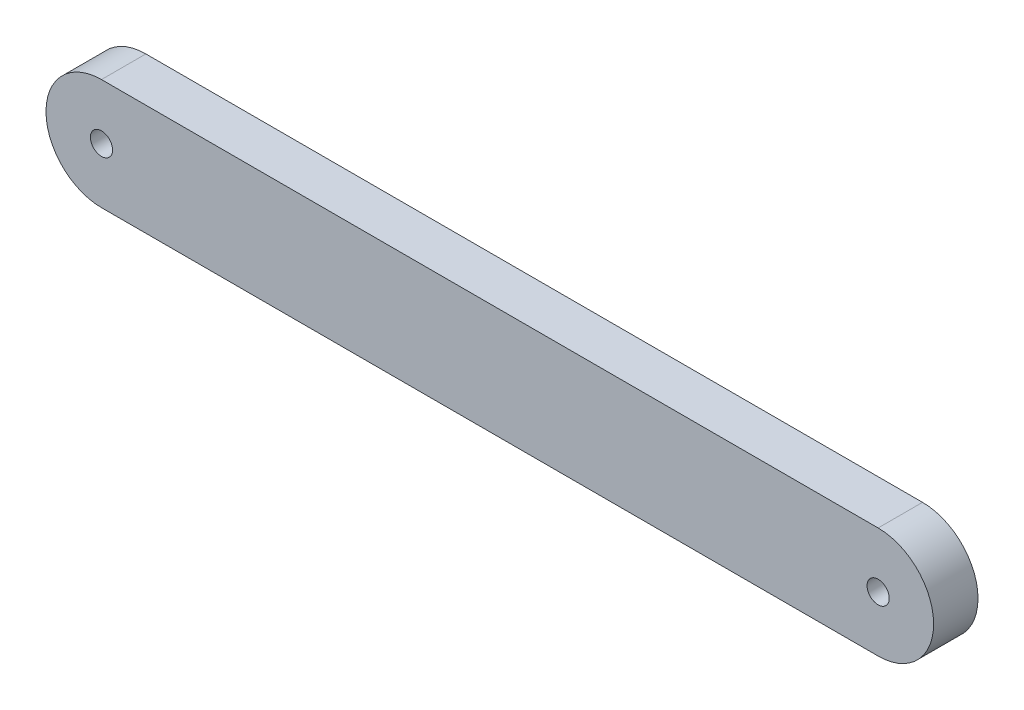
SolidWorks part; units mm, degrees
ref_plane "Front Plane" through (0, 0, 0) normal (0, 0, 1) x (1, 0, 0)
ref_plane "Top Plane" through (0, 0, 0) normal (0, 1, 0) x (1, 0, 0)
ref_plane "Right Plane" through (0, 0, 0) normal (1, 0, 0) x (0, 0, -1)
sketch "Sketch1" plane through (0, 0, 0) normal (0, 0, 1) x (1, 0, 0)
  line L0 (-444.5, 0) -> (444.5, 0) construction
  line L1 (-444.5, 63.5) -> (444.5, 63.5)
  line L2 (-444.5, -63.5) -> (444.5, -63.5)
  arc A0 (-444.5, 63.5) -> (-444.5, -63.5) centre (-444.5, 0) ccw
  arc A1 (444.5, -63.5) -> (444.5, 63.5) centre (444.5, 0) ccw
  point P2 (0, 0)
  point P8 (-508, 0)
  dimension "D1" = 889
  dimension "D2" = 63.5
extrude "Boss-Extrude1" add sketch "Sketch1" along normal blind 50.8
sketch "Sketch2" plane through (0, 0, 0) normal (0, 0, -1) x (-1, 0, 0)
  circle A0 centre (444.5, 0) radius 12.7
  circle A1 centre (-444.5, 0) radius 12.7
  dimension "D1" = 25.4
  dimension "D2" = 25.4
extrude "Cut-Extrude1" cut sketch "Sketch2" against normal through all
